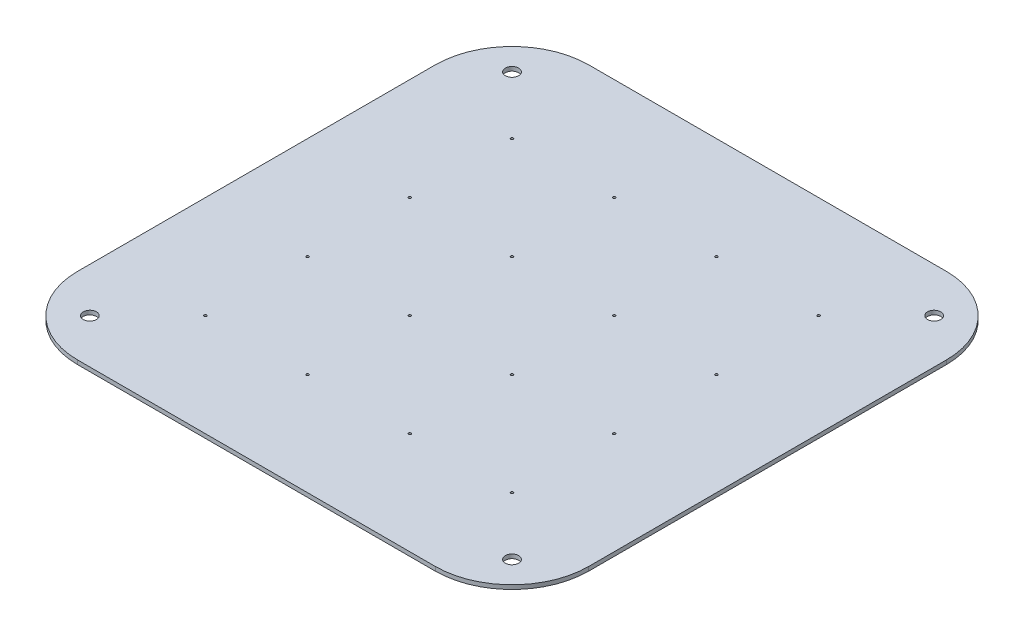
SolidWorks part; units mm, degrees
ref_plane "Front Plane" through (0, 0, 0) normal (0, 0, 1) x (1, 0, 0)
ref_plane "Top Plane" through (0, 0, 0) normal (0, 1, 0) x (1, 0, 0)
ref_plane "Right Plane" through (0, 0, 0) normal (1, 0, 0) x (0, 0, -1)
sketch "Sketch1" plane through (0, 0, 0) normal (0, 1, 0) x (1, 0, 0)
  line L0 (-80, 100) -> (-80, -100) construction
  line L1 (70, -100) -> (-70, -100)
  line L2 (100, -70) -> (100, 70)
  line L3 (70, 100) -> (-70, 100)
  line L4 (-100, -70) -> (-100, 70)
  line L5 (100, -100) -> (-100, 100) construction
  line L6 (100, 100) -> (-100, -100) construction
  line L7 (80, 100) -> (80, -100) construction
  line L8 (-100, 80) -> (100, 80) construction
  line L9 (-100, -80) -> (100, -80) construction
  line L10 (-100, 0) -> (100, 0) construction
  line L11 (-100, 40) -> (100, 40) construction
  line L12 (-100, -40) -> (100, -40) construction
  line L13 (0, 100) -> (0, -100) construction
  line L14 (-40, 100) -> (-40, -100) construction
  line L15 (40, 100) -> (40, -100) construction
  line L16 (-42.5, 70) -> (-42.5, 50)
  line L17 (-50, 2.5) -> (-70, 2.5)
  line L18 (-42.5, 10) -> (-42.5, 30)
  line L19 (-50, 37.5) -> (-70, 37.5)
  line L20 (-77.5, 10) -> (-77.5, 30)
  line L21 (-42.5, 2.5) -> (-77.5, 37.5) construction
  line L22 (-42.5, 37.5) -> (-77.5, 2.5) construction
  line L23 (-50, 42.5) -> (-70, 42.5)
  line L24 (-77.5, 70) -> (-77.5, 50)
  line L25 (-50, 77.5) -> (-70, 77.5)
  line L26 (-30, 77.5) -> (-10, 77.5)
  line L27 (-2.5, 70) -> (-2.5, 50)
  line L28 (-37.5, 70) -> (-37.5, 50)
  line L29 (-30, 42.5) -> (-10, 42.5)
  line L30 (-30, 37.5) -> (-10, 37.5)
  line L31 (-37.5, 10) -> (-37.5, 30)
  line L32 (-30, 2.5) -> (-10, 2.5)
  line L33 (-2.5, 10) -> (-2.5, 30)
  line L34 (42.5, 10) -> (42.5, 30)
  line L35 (50, 2.5) -> (70, 2.5)
  line L36 (77.5, 10) -> (77.5, 30)
  line L37 (50, 37.5) -> (70, 37.5)
  line L38 (42.5, 70) -> (42.5, 50)
  line L39 (50, 77.5) -> (70, 77.5)
  line L40 (77.5, 70) -> (77.5, 50)
  line L41 (50, 42.5) -> (70, 42.5)
  line L42 (2.5, 70) -> (2.5, 50)
  line L43 (30, 77.5) -> (10, 77.5)
  line L44 (37.5, 70) -> (37.5, 50)
  line L45 (30, 42.5) -> (10, 42.5)
  line L46 (37.5, 10) -> (37.5, 30)
  line L47 (30, 37.5) -> (10, 37.5)
  line L48 (2.5, 10) -> (2.5, 30)
  line L49 (30, 2.5) -> (10, 2.5)
  line L50 (-42.5, -70) -> (-42.5, -50)
  line L51 (-50, -77.5) -> (-70, -77.5)
  line L52 (-77.5, -70) -> (-77.5, -50)
  line L53 (-50, -42.5) -> (-70, -42.5)
  line L54 (-2.5, -70) -> (-2.5, -50)
  line L55 (-30, -77.5) -> (-10, -77.5)
  line L56 (-37.5, -70) -> (-37.5, -50)
  line L57 (-30, -42.5) -> (-10, -42.5)
  line L58 (37.5, -70) -> (37.5, -50)
  line L59 (30, -77.5) -> (10, -77.5)
  line L60 (2.5, -70) -> (2.5, -50)
  line L61 (30, -42.5) -> (10, -42.5)
  line L62 (77.5, -70) -> (77.5, -50)
  line L63 (50, -77.5) -> (70, -77.5)
  line L64 (42.5, -70) -> (42.5, -50)
  line L65 (50, -42.5) -> (70, -42.5)
  line L66 (50, -37.5) -> (70, -37.5)
  line L67 (77.5, -10) -> (77.5, -30)
  line L68 (50, -2.5) -> (70, -2.5)
  line L69 (42.5, -10) -> (42.5, -30)
  line L70 (37.5, -10) -> (37.5, -30)
  line L71 (30, -2.5) -> (10, -2.5)
  line L72 (2.5, -10) -> (2.5, -30)
  line L73 (30, -37.5) -> (10, -37.5)
  line L74 (-30, -37.5) -> (-10, -37.5)
  line L75 (-37.5, -10) -> (-37.5, -30)
  line L76 (-2.5, -10) -> (-2.5, -30)
  line L77 (-30, -2.5) -> (-10, -2.5)
  line L78 (-42.5, -10) -> (-42.5, -30)
  line L79 (-50, -37.5) -> (-70, -37.5)
  line L80 (-77.5, -10) -> (-77.5, -30)
  line L81 (-50, -2.5) -> (-70, -2.5)
  arc A0 (100, 70) -> (70, 100) centre (70, 70) ccw
  arc A1 (70, -100) -> (100, -70) centre (70, -70) ccw
  arc A2 (-70, -100) -> (-100, -70) centre (-70, -70) cw
  arc A3 (-70, 100) -> (-100, 70) centre (-70, 70) ccw
  circle A4 centre (-82.6, 82.6) radius 2.6
  circle A5 centre (82.6, 82.6) radius 2.6
  circle A6 centre (82.6, -82.6) radius 2.6
  circle A7 centre (-82.6, -82.6) radius 2.6
  arc A8 (-70, 2.5) -> (-77.5, 10) centre (-70, 10) cw
  arc A9 (-50, 2.5) -> (-42.5, 10) centre (-50, 10) ccw
  arc A10 (-42.5, 30) -> (-50, 37.5) centre (-50, 30) ccw
  arc A11 (-70, 37.5) -> (-77.5, 30) centre (-70, 30) ccw
  arc A12 (-50, 77.5) -> (-42.5, 70) centre (-50, 70) cw
  arc A13 (-42.5, 50) -> (-50, 42.5) centre (-50, 50) cw
  arc A14 (-70, 42.5) -> (-77.5, 50) centre (-70, 50) cw
  arc A15 (-70, 77.5) -> (-77.5, 70) centre (-70, 70) ccw
  arc A16 (-30, 77.5) -> (-37.5, 70) centre (-30, 70) ccw
  arc A17 (-10, 77.5) -> (-2.5, 70) centre (-10, 70) cw
  arc A18 (-37.5, 50) -> (-30, 42.5) centre (-30, 50) ccw
  arc A19 (-10, 42.5) -> (-2.5, 50) centre (-10, 50) ccw
  arc A20 (-10, 37.5) -> (-2.5, 30) centre (-10, 30) cw
  arc A21 (-37.5, 30) -> (-30, 37.5) centre (-30, 30) cw
  arc A22 (-30, 2.5) -> (-37.5, 10) centre (-30, 10) cw
  arc A23 (-10, 2.5) -> (-2.5, 10) centre (-10, 10) ccw
  arc A24 (42.5, 30) -> (50, 37.5) centre (50, 30) cw
  arc A25 (50, 2.5) -> (42.5, 10) centre (50, 10) cw
  arc A26 (70, 2.5) -> (77.5, 10) centre (70, 10) ccw
  arc A27 (70, 37.5) -> (77.5, 30) centre (70, 30) cw
  arc A28 (50, 77.5) -> (42.5, 70) centre (50, 70) ccw
  arc A29 (70, 77.5) -> (77.5, 70) centre (70, 70) cw
  arc A30 (70, 42.5) -> (77.5, 50) centre (70, 50) ccw
  arc A31 (42.5, 50) -> (50, 42.5) centre (50, 50) ccw
  arc A32 (10, 42.5) -> (2.5, 50) centre (10, 50) cw
  arc A33 (10, 77.5) -> (2.5, 70) centre (10, 70) ccw
  arc A34 (30, 77.5) -> (37.5, 70) centre (30, 70) cw
  arc A35 (37.5, 50) -> (30, 42.5) centre (30, 50) cw
  arc A36 (37.5, 30) -> (30, 37.5) centre (30, 30) ccw
  arc A37 (10, 37.5) -> (2.5, 30) centre (10, 30) ccw
  arc A38 (10, 2.5) -> (2.5, 10) centre (10, 10) cw
  arc A39 (30, 2.5) -> (37.5, 10) centre (30, 10) ccw
  arc A40 (-42.5, -50) -> (-50, -42.5) centre (-50, -50) ccw
  arc A41 (-50, -77.5) -> (-42.5, -70) centre (-50, -70) ccw
  arc A42 (-70, -77.5) -> (-77.5, -70) centre (-70, -70) cw
  arc A43 (-70, -42.5) -> (-77.5, -50) centre (-70, -50) ccw
  arc A44 (-10, -77.5) -> (-2.5, -70) centre (-10, -70) ccw
  arc A45 (-30, -77.5) -> (-37.5, -70) centre (-30, -70) cw
  arc A46 (-37.5, -50) -> (-30, -42.5) centre (-30, -50) cw
  arc A47 (-10, -42.5) -> (-2.5, -50) centre (-10, -50) cw
  arc A48 (37.5, -50) -> (30, -42.5) centre (30, -50) ccw
  arc A49 (30, -77.5) -> (37.5, -70) centre (30, -70) ccw
  arc A50 (10, -77.5) -> (2.5, -70) centre (10, -70) cw
  arc A51 (10, -42.5) -> (2.5, -50) centre (10, -50) ccw
  arc A52 (70, -42.5) -> (77.5, -50) centre (70, -50) cw
  arc A53 (70, -77.5) -> (77.5, -70) centre (70, -70) ccw
  arc A54 (50, -77.5) -> (42.5, -70) centre (50, -70) cw
  arc A55 (42.5, -50) -> (50, -42.5) centre (50, -50) cw
  arc A56 (70, -37.5) -> (77.5, -30) centre (70, -30) ccw
  arc A57 (70, -2.5) -> (77.5, -10) centre (70, -10) cw
  arc A58 (50, -2.5) -> (42.5, -10) centre (50, -10) ccw
  arc A59 (42.5, -30) -> (50, -37.5) centre (50, -30) ccw
  arc A60 (37.5, -30) -> (30, -37.5) centre (30, -30) cw
  arc A61 (30, -2.5) -> (37.5, -10) centre (30, -10) cw
  arc A62 (10, -2.5) -> (2.5, -10) centre (10, -10) ccw
  arc A63 (10, -37.5) -> (2.5, -30) centre (10, -30) cw
  arc A64 (-10, -37.5) -> (-2.5, -30) centre (-10, -30) ccw
  arc A65 (-37.5, -30) -> (-30, -37.5) centre (-30, -30) ccw
  arc A66 (-10, -2.5) -> (-2.5, -10) centre (-10, -10) cw
  arc A67 (-30, -2.5) -> (-37.5, -10) centre (-30, -10) ccw
  arc A68 (-50, -2.5) -> (-42.5, -10) centre (-50, -10) cw
  arc A69 (-42.5, -30) -> (-50, -37.5) centre (-50, -30) cw
  arc A70 (-70, -37.5) -> (-77.5, -30) centre (-70, -30) cw
  arc A71 (-70, -2.5) -> (-77.5, -10) centre (-70, -10) ccw
  circle A72 centre (-60, 60) radius 0.5
  circle A73 centre (-20, 60) radius 0.5
  circle A74 centre (-20, 20) radius 0.5
  circle A75 centre (-60, 20) radius 0.5
  circle A76 centre (60, 20) radius 0.5
  circle A77 centre (20, 20) radius 0.5
  circle A78 centre (20, 60) radius 0.5
  circle A79 centre (60, 60) radius 0.5
  circle A80 centre (20, -20) radius 0.5
  circle A81 centre (60, -20) radius 0.5
  circle A82 centre (60, -60) radius 0.5
  circle A83 centre (20, -60) radius 0.5
  circle A84 centre (-20, -20) radius 0.5
  circle A85 centre (-60, -20) radius 0.5
  circle A86 centre (-20, -60) radius 0.5
  circle A87 centre (-60, -60) radius 0.5
  point P0 (0, 0)
  point P25 (-60, 20)
  dimension "D15" = 30
  dimension "D16" = 5.2
  dimension "D19" = 5.2
  dimension "D20" = 5.2
  dimension "D22" = 5.2
  dimension "D24" = 7.5
  dimension "D26" = 1
  dimension "D27" = 1
  dimension "D1" = 200
  dimension "D2" = 200
  dimension "D3" = 20
  dimension "D4" = 20
  dimension "D5" = 20
  dimension "D6" = 20
  dimension "D7" = 40
  dimension "D8" = 40
  dimension "D9" = 40
  dimension "D10" = 40
  dimension "D11" = 20
  dimension "D12" = 20
  dimension "D13" = 35
  dimension "D14" = 35
  dimension "D17" = 2.6
  dimension "D18" = 2.6
  dimension "D21" = 2.6
  dimension "D23" = 2.6
  dimension "D25" = 0
  dimension "D28" = 17.5
  dimension "D29" = 17.5
  dimension "D30" = 17.5
extrude "Boss-Extrude1" add sketch "Sketch1" along normal blind 1.6 contours L3 A3 L4 A2 L1 A1 L2 A0 A71 L81 A68 L78 A69 L79 A70 L80 A67 L77 A66 L76 A64 L74 A65 L75 A59 L69 A58 L68 A57 L67 A56 L66 A51 L61 A48 L58 A49 L59 A50 L60 A43 L53 A40 L50 A41 L51 | L25 A15 L24 A14 L23 A13 L16 A12 A72 | L29 A19 L27 A17 L26 A16 L28 A18 A73 | A35 L44 A34 L43 A33 L42 A32 L45 A78 | L38 A31 L41 A30 L40 A29 L39 A28 A79 | A27 L37 A24 L34 A25 L35 A26 L36 A76 | L49 A39 L46 A36 L47 A37 L48 A38 A77 | L19 A11 L20 A8 L17 A9 L18 A10 A75 | L81 A71 L80 A70 L79 A69 L78 A68 A85 | L77 A67 L75 A65 L74 A64 L76 A66 A84 | A63 L73 A60 L70 A61 L71 A62 L72 A80 | L69 A59 L66 A56 L67 A57 L68 A58 A81 | A55 L64 A54 L63 A53 L62 A52 L65 A82 | L61 A51 L60 A50 L59 A49 L58 A48 A83 | A47 L57 A46 L56 A45 L55 A44 L54 A86 | L53 A43 L52 A42 L51 A41 L50 A40 A87 | L32 A23 L33 A20 L30 A21 L31 A22 A74
